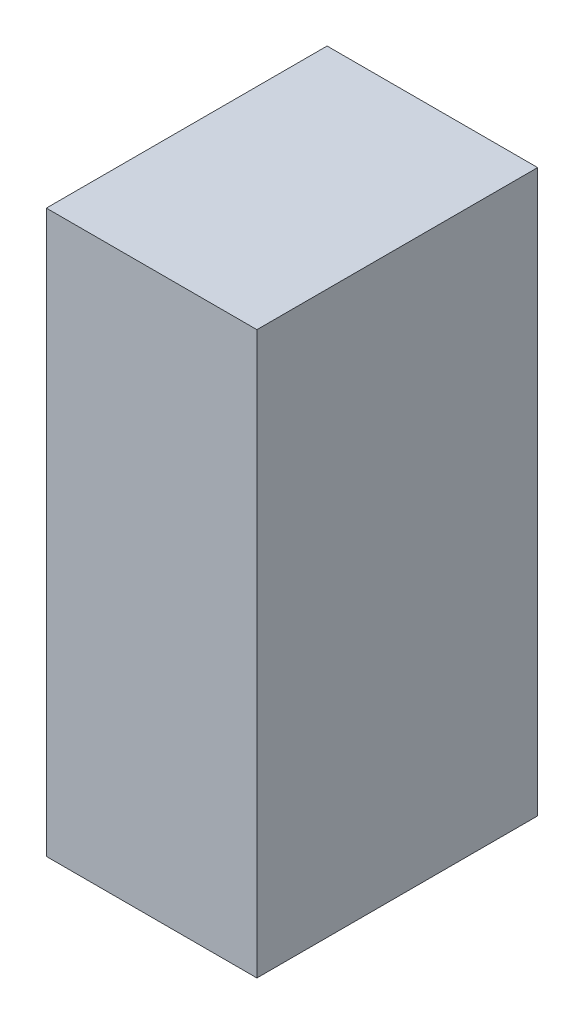
SolidWorks part; units mm, degrees
material "轻木"
ref_plane "前视基准面" through (0, 0, 0) normal (0, 0, 1) x (1, 0, 0)
ref_plane "上视基准面" through (0, 0, 0) normal (0, 1, 0) x (1, 0, 0)
ref_plane "右视基准面" through (0, 0, 0) normal (1, 0, 0) x (0, 0, -1)
other "Configuration Table"
sketch "草图1" plane through (0, 0, 0) normal (0, 1, 0) x (1, 0, 0)
  line L0 (0, 0) -> (1.5, 0)
  line L1 (1.5, 0) -> (1.5, -2)
  line L2 (0, 0) -> (0, -2)
  line L3 (0, -2) -> (1.5, -2)
extrude "凸台-拉伸1" add sketch "草图1" along normal blind 4
